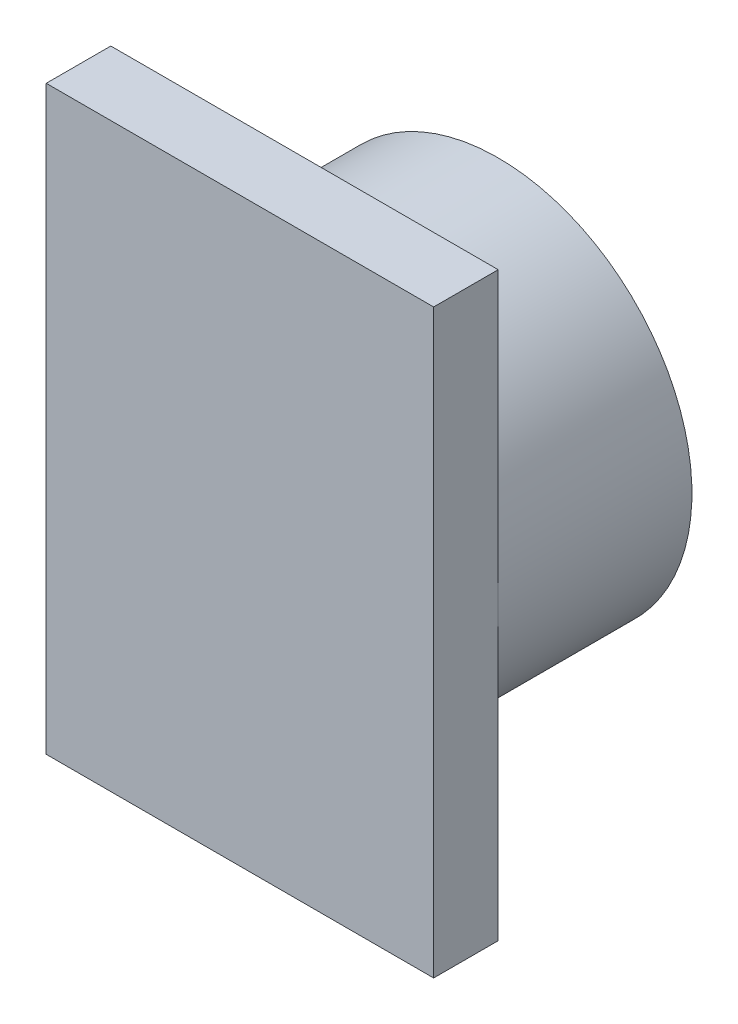
SolidWorks part; units mm, degrees
ref_plane "Front Plane" through (0, 0, 0) normal (0, 0, 1) x (1, 0, 0)
ref_plane "Top Plane" through (0, 0, 0) normal (0, 1, 0) x (1, 0, 0)
ref_plane "Right Plane" through (0, 0, 0) normal (1, 0, 0) x (0, 0, -1)
sketch "Sketch1" plane through (0, 0, 0) normal (0, 0, 1) x (1, 0, 0)
  line L1 (-30, -45) -> (30, -45)
  line L2 (-30, -45) -> (-30, 45)
  line L3 (-30, 45) -> (30, 45)
  line L4 (30, -45) -> (30, 45)
  line L5 (-30, -45) -> (30, 45) construction
  line L6 (-30, 45) -> (30, -45) construction
  point P0 (0, 0)
  dimension "D1" = 60
  dimension "D2" = 90
extrude "Boss-Extrude1" add sketch "Sketch1" along normal blind 10
sketch "Sketch2" plane through (0, 0, 0) normal (0, 0, -1) x (-1, 0, 0)
  line L0 (4, -13.9127) -> (4, -13.3253)
  line L3 (-4, -16.9127) -> (4, -16.9127)
  line L4 (4, -13.9127) -> (4, -16.9127)
  line L5 (-4, -13.9127) -> (-4, -13.3253)
  line L6 (-4, -13.9127) -> (-4, -16.9127)
  circle A0 centre (0, 0) radius 30
  arc A1 (4, -13.3253) -> (-4, -13.3253) centre (0, 0) ccw
  dimension "D1" = 60
  dimension "D2" = 3
extrude "Boss-Extrude2" add sketch "Sketch2" along normal blind 30
sketch "Sketch6" plane through (0, 45, 0) normal (0, 1, 0) x (1, 0, 0)
  circle A0 centre (0, -28.6) radius 13.5614
  circle A1 centre (0, -28.6) radius 23
